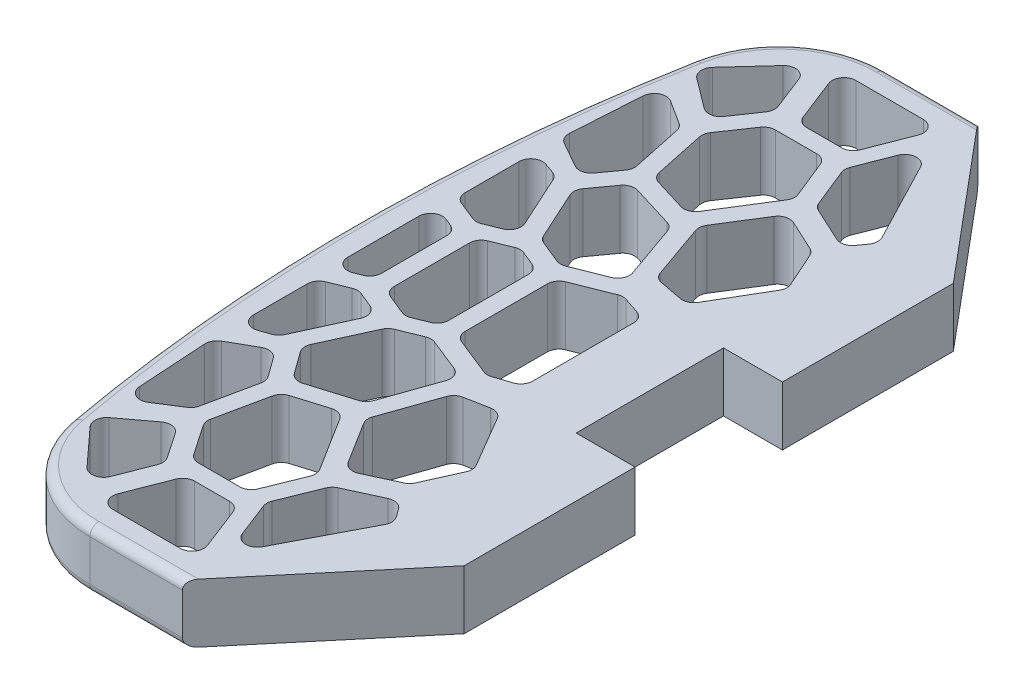
SolidWorks part; units mm, degrees
ref_plane "Спереди" through (0, 0, 0) normal (0, 0, 1) x (1, 0, 0)
ref_plane "Сверху" through (0, 0, 0) normal (0, 1, 0) x (1, 0, 0)
ref_plane "Справа" through (0, 0, 0) normal (1, 0, 0) x (0, 0, -1)
other "Configuration Table"
sketch "Sketch1" plane through (0, 0, 0) normal (0, 1, 0) x (1, 0, 0)
  line L0 (0, 83) -> (-43.6332, 135)
  line L1 (-120, 135) -> (0, 135) construction
  line L3 (-120, -135) -> (0, -135) construction
  line L4 (0, 135) -> (0, -135) construction
  line L5 (-43.6332, 135) -> (-75, 135)
  line L6 (0, -83) -> (-43.6332, -135)
  line L7 (0, 83) -> (0, 25)
  line L8 (0, 25) -> (-20, 25)
  line L9 (-20, 25) -> (-20, -25)
  line L10 (-20, -25) -> (0, -25)
  line L11 (-134.8601, 0) -> (61.7365, 0) construction
  line L12 (-89.1294, -199.9223) -> (-89.1294, 67.4111) construction
  line L13 (-120, 135) -> (-120, -135) construction
  line L14 (-43.6332, -135) -> (-75, -135)
  line L15 (0, -83) -> (0, -25)
  line L16 (-51.5835, -99.5519) -> (-47.044, -111.2449)
  line L17 (-39.7668, -111.6438) -> (-25.558, -84.3396)
  line L18 (-32.7123, -76.168) -> (-44.2897, -81.4925)
  line L19 (-46.3278, -83.6299) -> (-51.5641, -96.6076)
  line L20 (-76.1692, -126.0674) -> (-53.2432, -126.0674)
  line L21 (-49.5143, -120.6197) -> (-55.0229, -106.4306)
  line L22 (-58.7518, -103.8782) -> (-70.6335, -103.8782)
  line L23 (-74.3599, -106.4244) -> (-79.8956, -120.6136)
  line L24 (-104.3144, -105.6227) -> (-92.9037, -118.071)
  line L25 (-86.2286, -116.822) -> (-81.7314, -105.2948)
  line L26 (-82.1529, -101.5877) -> (-87.9561, -93.0762)
  line L27 (-93.6634, -92.1313) -> (-103.7682, -99.7216)
  line L28 (-110.4098, -12.0561) -> (-110.4098, 12.0561)
  line L29 (-104.9035, 15.7616) -> (-102.4473, 14.7632)
  line L30 (-99.9536, 11.0577) -> (-99.9536, -11.0577)
  line L31 (-102.4473, -14.7632) -> (-104.9035, -15.7616)
  line L32 (-91.46, 16.4616) -> (-84.9311, 19.1157)
  line L33 (-81.9184, 19.1157) -> (-77.2039, 17.1992)
  line L34 (-74.7102, 13.4937) -> (-74.7102, -13.4937)
  line L35 (-77.2039, -17.1992) -> (-81.9184, -19.1157)
  line L36 (-84.9311, -19.1157) -> (-91.46, -16.4616)
  line L37 (-93.9536, -12.7561) -> (-93.9536, 12.7561)
  line L38 (-68.7102, -13.9388) -> (-68.7102, 13.9388)
  line L39 (-66.193, 17.6539) -> (-53.5974, 22.6809)
  line L40 (-50.851, 22.761) -> (-45.3523, 20.93)
  line L41 (-42.6161, 17.1349) -> (-42.6161, -17.1349)
  line L42 (-45.3523, -20.93) -> (-50.851, -22.761)
  line L43 (-53.5974, -22.6809) -> (-66.193, -17.6539)
  line L44 (-109.4672, -45.085) -> (-109.4672, -26.7855)
  line L45 (-106.9735, -23.0799) -> (-100.549, -20.4683)
  line L46 (-97.5364, -20.4683) -> (-92.4294, -22.5443)
  line L47 (-90.2975, -27.912) -> (-98.3379, -45.5117)
  line L48 (-100.6417, -47.6203) -> (-104.1327, -48.8558)
  line L49 (-91.0282, -43.9506) -> (-83.4663, -27.3984)
  line L50 (-81.3343, -25.355) -> (-73.7854, -22.2863)
  line L51 (-70.7963, -22.2768) -> (-59.788, -26.6704)
  line L52 (-57.4974, -31.7129) -> (-63.8788, -49.851)
  line L53 (-66.4825, -52.3487) -> (-80.926, -56.7647)
  line L54 (-85.3376, -55.2823) -> (-90.6321, -47.9556)
  line L55 (-109.1859, -61.8731) -> (-107.7167, -85.4548)
  line L56 (-101.576, -88.5801) -> (-93.5679, -83.481)
  line L57 (-91.8022, -80.9315) -> (-88.1953, -63.8092)
  line L58 (-88.8673, -60.6419) -> (-93.373, -54.4066)
  line L59 (-98.5914, -53.2717) -> (-107.1699, -58.1467)
  line L60 (-59.2517, -54.778) -> (-52.7411, -36.2726)
  line L61 (-49.7099, -33.6696) -> (-41.8514, -32.1859)
  line L62 (-37.6591, -34.0926) -> (-27.4855, -51.4361)
  line L63 (-27.2853, -55.0953) -> (-32.5729, -66.8979)
  line L64 (-34.5425, -68.8922) -> (-45.0179, -73.7431)
  line L65 (-50.088, -72.2377) -> (-58.8677, -58.2299)
  line L66 (-86.0989, -82.9648) -> (-82.4552, -65.668)
  line L67 (-79.7106, -62.6673) -> (-68.759, -59.3189)
  line L68 (-64.2002, -61.0198) -> (-52.797, -79.2134)
  line L69 (-52.4768, -82.8344) -> (-57.5367, -95.3749)
  line L70 (-61.2462, -97.8782) -> (-75.3061, -97.8782)
  line L71 (-78.6111, -96.1315) -> (-85.4897, -86.0427)
  line L72 (-27.7933, -77.4671) -> (-25.8585, -80.1581)
  line L73 (-27.7933, 77.4671) -> (-25.8585, 80.1581)
  line L74 (-78.6111, 96.1315) -> (-85.4897, 86.0427)
  line L75 (-61.2462, 97.8782) -> (-75.3061, 97.8782)
  line L76 (-52.4768, 82.8344) -> (-57.5367, 95.3749)
  line L77 (-64.2002, 61.0198) -> (-52.797, 79.2134)
  line L78 (-79.7106, 62.6673) -> (-68.759, 59.3189)
  line L79 (-86.0989, 82.9648) -> (-82.4552, 65.668)
  line L80 (-50.088, 72.2377) -> (-58.8677, 58.2299)
  line L81 (-34.5425, 68.8922) -> (-45.0179, 73.7431)
  line L82 (-27.2853, 55.0953) -> (-32.5729, 66.8979)
  line L83 (-37.6591, 34.0926) -> (-27.4855, 51.4361)
  line L84 (-49.7099, 33.6696) -> (-41.8514, 32.1859)
  line L85 (-59.2517, 54.778) -> (-52.7411, 36.2726)
  line L86 (-98.5914, 53.2717) -> (-107.1699, 58.1467)
  line L87 (-88.8673, 60.6419) -> (-93.373, 54.4066)
  line L88 (-91.8022, 80.9315) -> (-88.1953, 63.8092)
  line L89 (-101.576, 88.5801) -> (-93.5679, 83.481)
  line L90 (-109.1859, 61.8731) -> (-107.7167, 85.4548)
  line L91 (-85.3376, 55.2823) -> (-90.6321, 47.9556)
  line L92 (-66.4825, 52.3487) -> (-80.926, 56.7647)
  line L93 (-57.4974, 31.7129) -> (-63.8788, 49.851)
  line L94 (-70.7963, 22.2768) -> (-59.788, 26.6704)
  line L95 (-81.3343, 25.355) -> (-73.7854, 22.2863)
  line L96 (-91.0282, 43.9506) -> (-83.4663, 27.3984)
  line L97 (-100.6417, 47.6203) -> (-104.1327, 48.8558)
  line L98 (-90.2975, 27.912) -> (-98.3379, 45.5117)
  line L99 (-97.5364, 20.4683) -> (-92.4294, 22.5443)
  line L100 (-106.9735, 23.0799) -> (-100.549, 20.4683)
  line L101 (-109.4672, 45.085) -> (-109.4672, 26.7855)
  line L102 (-93.6634, 92.1313) -> (-103.7682, 99.7216)
  line L103 (-82.1529, 101.5877) -> (-87.9561, 93.0762)
  line L104 (-86.2286, 116.822) -> (-81.7314, 105.2948)
  line L105 (-104.3144, 105.6227) -> (-92.9037, 118.071)
  line L106 (-74.3599, 106.4244) -> (-79.8956, 120.6136)
  line L107 (-58.7518, 103.8782) -> (-70.6335, 103.8782)
  line L108 (-49.5143, 120.6197) -> (-55.0229, 106.4306)
  line L109 (-76.1692, 126.0674) -> (-53.2432, 126.0674)
  line L110 (-46.3278, 83.6299) -> (-51.5641, 96.6076)
  line L111 (-32.7123, 76.168) -> (-44.2897, 81.4925)
  line L112 (-39.7668, 111.6438) -> (-25.558, 84.3396)
  line L113 (-51.5835, 99.5519) -> (-47.044, 111.2449)
  line L114 (-43.6332, 135) -> (-75, 135)
  arc A0 (-75, 135) -> (-110.4098, 105.4918) centre (-75, 99) ccw
  arc A1 (-110.4098, 105.4918) -> (-110.4098, -105.4918) centre (465, 0) ccw
  arc A2 (-75, -135) -> (-110.4098, -105.4918) centre (-75, -99) cw
  arc A3 (-59.2517, -54.778) -> (-58.8677, -58.2299) centre (-55.4784, -56.1056) ccw
  arc A4 (-52.7411, -36.2726) -> (-49.7099, -33.6696) centre (-48.9678, -37.6002) cw
  arc A5 (-41.8514, -32.1859) -> (-37.6591, -34.0926) centre (-41.1093, -36.1164) cw
  arc A6 (-27.4855, -51.4361) -> (-27.2853, -55.0953) centre (-30.9357, -53.4599) cw
  arc A7 (-32.5729, -66.8979) -> (-34.5425, -68.8922) centre (-36.2233, -65.2625) cw
  arc A8 (-45.0179, -73.7431) -> (-50.088, -72.2377) centre (-46.6987, -70.1134) cw
  arc A9 (-25.8585, -80.1581) -> (-25.558, -84.3396) centre (-29.1062, -82.4931) cw
  arc A10 (-27.7933, -77.4671) -> (-32.7123, -76.168) centre (-31.041, -79.8021) ccw
  arc A11 (-44.2897, -81.4925) -> (-46.3278, -83.6299) centre (-42.6184, -85.1266) ccw
  arc A12 (-51.5835, -99.5519) -> (-51.5641, -96.6076) centre (-47.8547, -98.1043) cw
  arc A13 (-47.044, -111.2449) -> (-39.7668, -111.6438) centre (-43.3151, -109.7973) ccw
  arc A14 (-53.2432, -126.0674) -> (-49.5143, -120.6197) centre (-53.2432, -122.0674) ccw
  arc A15 (-76.1692, -126.0674) -> (-79.8956, -120.6136) centre (-76.1692, -122.0674) cw
  arc A16 (-55.0229, -106.4306) -> (-58.7518, -103.8782) centre (-58.7518, -107.8782) ccw
  arc A17 (-70.6335, -103.8782) -> (-74.3599, -106.4244) centre (-70.6335, -107.8782) ccw
  arc A18 (-52.797, -79.2134) -> (-52.4768, -82.8344) centre (-56.1863, -81.3377) cw
  arc A19 (-57.5367, -95.3749) -> (-61.2462, -97.8782) centre (-61.2462, -93.8782) cw
  arc A20 (-75.3061, -97.8782) -> (-78.6111, -96.1315) centre (-75.3061, -93.8782) cw
  arc A21 (-86.0989, -82.9648) -> (-85.4897, -86.0427) centre (-82.1848, -83.7894) ccw
  arc A22 (-68.759, -59.3189) -> (-64.2002, -61.0198) centre (-67.5895, -63.1441) cw
  arc A23 (-82.4552, -65.668) -> (-79.7106, -62.6673) centre (-78.5411, -66.4925) cw
  arc A24 (-93.5679, -83.481) -> (-91.8022, -80.9315) centre (-95.7163, -80.1069) ccw
  arc A25 (-88.1953, -63.8092) -> (-88.8673, -60.6419) centre (-92.1094, -62.9847) ccw
  arc A26 (-93.373, -54.4066) -> (-98.5914, -53.2717) centre (-96.6151, -56.7494) ccw
  arc A27 (-81.7314, -105.2948) -> (-82.1529, -101.5877) centre (-85.4578, -103.841) ccw
  arc A28 (-87.9561, -93.0762) -> (-93.6634, -92.1313) centre (-91.261, -95.3295) ccw
  arc A29 (-92.9037, -118.071) -> (-86.2286, -116.822) centre (-89.955, -115.3682) ccw
  arc A30 (-104.3144, -105.6227) -> (-103.7682, -99.7216) centre (-101.3658, -102.9198) cw
  arc A31 (-109.1859, -61.8731) -> (-107.1699, -58.1467) centre (-105.1936, -61.6244) cw
  arc A32 (-107.7167, -85.4548) -> (-101.576, -88.5801) centre (-103.7245, -85.2061) ccw
  arc A33 (-80.926, -56.7647) -> (-85.3376, -55.2823) centre (-82.0955, -52.9395) cw
  arc A34 (-63.8788, -49.851) -> (-66.4825, -52.3487) centre (-67.6521, -48.5235) cw
  arc A35 (-59.788, -26.6704) -> (-57.4974, -31.7129) centre (-61.2707, -30.3854) cw
  arc A36 (-73.7854, -22.2863) -> (-70.7963, -22.2768) centre (-72.279, -25.9919) cw
  arc A37 (-83.4663, -27.3984) -> (-81.3343, -25.355) centre (-79.828, -29.0606) cw
  arc A38 (-91.0282, -43.9506) -> (-90.6321, -47.9556) centre (-87.3899, -45.6128) ccw
  arc A39 (-98.3379, -45.5117) -> (-100.6417, -47.6203) centre (-101.9762, -43.8495) cw
  arc A40 (-109.4672, -45.085) -> (-104.1327, -48.8558) centre (-105.4672, -45.085) ccw
  arc A41 (-92.4294, -22.5443) -> (-90.2975, -27.912) centre (-93.9358, -26.2499) cw
  arc A42 (-100.549, -20.4683) -> (-97.5364, -20.4683) centre (-99.0427, -24.1739) cw
  arc A43 (-109.4672, -26.7855) -> (-106.9735, -23.0799) centre (-105.4672, -26.7855) cw
  arc A44 (-74.7102, -13.4937) -> (-77.2039, -17.1992) centre (-78.7102, -13.4937) cw
  arc A45 (-91.46, -16.4616) -> (-93.9536, -12.7561) centre (-89.9536, -12.7561) cw
  arc A46 (-81.9184, -19.1157) -> (-84.9311, -19.1157) centre (-83.4248, -15.4101) cw
  arc A47 (-42.6161, -17.1349) -> (-45.3523, -20.93) centre (-46.6161, -17.1349) cw
  arc A48 (-50.851, -22.761) -> (-53.5974, -22.6809) centre (-52.1147, -18.9659) cw
  arc A49 (-68.7102, -13.9388) -> (-66.193, -17.6539) centre (-64.7102, -13.9388) ccw
  arc A50 (-45.3523, 20.93) -> (-42.6161, 17.1349) centre (-46.6161, 17.1349) cw
  arc A51 (-53.5974, 22.6809) -> (-50.851, 22.761) centre (-52.1147, 18.9659) cw
  arc A52 (-68.7102, 13.9388) -> (-66.193, 17.6539) centre (-64.7102, 13.9388) cw
  arc A53 (-77.2039, 17.1992) -> (-74.7102, 13.4937) centre (-78.7102, 13.4937) cw
  arc A54 (-84.9311, 19.1157) -> (-81.9184, 19.1157) centre (-83.4248, 15.4101) cw
  arc A55 (-91.46, 16.4616) -> (-93.9536, 12.7561) centre (-89.9536, 12.7561) ccw
  arc A56 (-99.9536, -11.0577) -> (-102.4473, -14.7632) centre (-103.9536, -11.0577) cw
  arc A57 (-110.4098, -12.0561) -> (-104.9035, -15.7616) centre (-106.4098, -12.0561) ccw
  arc A58 (-102.4473, 14.7632) -> (-99.9536, 11.0577) centre (-103.9536, 11.0577) cw
  arc A59 (-110.4098, 12.0561) -> (-104.9035, 15.7616) centre (-106.4098, 12.0561) cw
  arc A60 (-109.4672, 26.7855) -> (-106.9735, 23.0799) centre (-105.4672, 26.7855) ccw
  arc A61 (-92.4294, 22.5443) -> (-90.2975, 27.912) centre (-93.9358, 26.2499) ccw
  arc A62 (-109.4672, 45.085) -> (-104.1327, 48.8558) centre (-105.4672, 45.085) cw
  arc A63 (-98.3379, 45.5117) -> (-100.6417, 47.6203) centre (-101.9762, 43.8495) ccw
  arc A64 (-91.0282, 43.9506) -> (-90.6321, 47.9556) centre (-87.3899, 45.6128) cw
  arc A65 (-83.4663, 27.3984) -> (-81.3343, 25.355) centre (-79.828, 29.0606) ccw
  arc A66 (-73.7854, 22.2863) -> (-70.7963, 22.2768) centre (-72.279, 25.9919) ccw
  arc A67 (-59.788, 26.6704) -> (-57.4974, 31.7129) centre (-61.2707, 30.3854) ccw
  arc A68 (-63.8788, 49.851) -> (-66.4825, 52.3487) centre (-67.6521, 48.5235) ccw
  arc A69 (-80.926, 56.7647) -> (-85.3376, 55.2823) centre (-82.0955, 52.9395) ccw
  arc A70 (-107.7167, 85.4548) -> (-101.576, 88.5801) centre (-103.7245, 85.2061) cw
  arc A71 (-109.1859, 61.8731) -> (-107.1699, 58.1467) centre (-105.1936, 61.6244) ccw
  arc A72 (-104.3144, 105.6227) -> (-103.7682, 99.7216) centre (-101.3658, 102.9198) ccw
  arc A73 (-92.9037, 118.071) -> (-86.2286, 116.822) centre (-89.955, 115.3682) cw
  arc A74 (-87.9561, 93.0762) -> (-93.6634, 92.1313) centre (-91.261, 95.3295) cw
  arc A75 (-81.7314, 105.2948) -> (-82.1529, 101.5877) centre (-85.4578, 103.841) cw
  arc A76 (-93.373, 54.4066) -> (-98.5914, 53.2717) centre (-96.6151, 56.7494) cw
  arc A77 (-88.1953, 63.8092) -> (-88.8673, 60.6419) centre (-92.1094, 62.9847) cw
  arc A78 (-93.5679, 83.481) -> (-91.8022, 80.9315) centre (-95.7163, 80.1069) cw
  arc A79 (-82.4552, 65.668) -> (-79.7106, 62.6673) centre (-78.5411, 66.4925) ccw
  arc A80 (-68.759, 59.3189) -> (-64.2002, 61.0198) centre (-67.5895, 63.1441) ccw
  arc A81 (-86.0989, 82.9648) -> (-85.4897, 86.0427) centre (-82.1848, 83.7894) cw
  arc A82 (-75.3061, 97.8782) -> (-78.6111, 96.1315) centre (-75.3061, 93.8782) ccw
  arc A83 (-57.5367, 95.3749) -> (-61.2462, 97.8782) centre (-61.2462, 93.8782) ccw
  arc A84 (-52.797, 79.2134) -> (-52.4768, 82.8344) centre (-56.1863, 81.3377) ccw
  arc A85 (-70.6335, 103.8782) -> (-74.3599, 106.4244) centre (-70.6335, 107.8782) cw
  arc A86 (-55.0229, 106.4306) -> (-58.7518, 103.8782) centre (-58.7518, 107.8782) cw
  arc A87 (-76.1692, 126.0674) -> (-79.8956, 120.6136) centre (-76.1692, 122.0674) ccw
  arc A88 (-53.2432, 126.0674) -> (-49.5143, 120.6197) centre (-53.2432, 122.0674) cw
  arc A89 (-47.044, 111.2449) -> (-39.7668, 111.6438) centre (-43.3151, 109.7973) cw
  arc A90 (-51.5835, 99.5519) -> (-51.5641, 96.6076) centre (-47.8547, 98.1043) ccw
  arc A91 (-44.2897, 81.4925) -> (-46.3278, 83.6299) centre (-42.6184, 85.1266) cw
  arc A92 (-27.7933, 77.4671) -> (-32.7123, 76.168) centre (-31.041, 79.8021) cw
  arc A93 (-25.8585, 80.1581) -> (-25.558, 84.3396) centre (-29.1062, 82.4931) ccw
  arc A94 (-45.0179, 73.7431) -> (-50.088, 72.2377) centre (-46.6987, 70.1134) ccw
  arc A95 (-32.5729, 66.8979) -> (-34.5425, 68.8922) centre (-36.2233, 65.2625) ccw
  arc A96 (-27.4855, 51.4361) -> (-27.2853, 55.0953) centre (-30.9357, 53.4599) ccw
  arc A97 (-41.8514, 32.1859) -> (-37.6591, 34.0926) centre (-41.1093, 36.1164) ccw
  arc A98 (-52.7411, 36.2726) -> (-49.7099, 33.6696) centre (-48.9678, 37.6002) ccw
  arc A99 (-59.2517, 54.778) -> (-58.8677, 58.2299) centre (-55.4784, 56.1056) cw
  arc A100 (-100.549, 20.4683) -> (-97.5364, 20.4683) centre (-99.0427, 24.1739) ccw
  point P155 (-99.0427, -47.0544)
  point P158 (-109.4672, -50.7438)
  point P193 (-110.4098, -18)
  point P198 (-110.4098, 18)
  point P199 (-100.3678, -46.2956)
  point P200 (0, 0)
  point P321 (-99.0427, 47.0544)
  dimension "D7" = 36
  dimension "D25" = 4
  dimension "D1" = 120
  dimension "D2" = 270
  dimension "D3" = 40
  dimension "D4" = 20
  dimension "D5" = 50
  dimension "D6" = 58
  dimension "D8" = 75
  dimension "D9" = 6
  dimension "D10" = 6
  dimension "D11" = 6
  dimension "D12" = 6
  dimension "D13" = 6
  dimension "D14" = 6
  dimension "D15" = 6
  dimension "D16" = 6
  dimension "D17" = 6
  dimension "D18" = 6
  dimension "D19" = 6
  dimension "D20" = 36
  dimension "D21" = 6
  dimension "D22" = 6
  dimension "D23" = 6
  dimension "D24" = 6
extrude "Boss-Extrude1" add sketch "Sketch1" along normal mid plane 20 contours A2 L14 L6 L15 L10 L9 L8 L7 L0 L5 A0 A1 A100 L100 A60 L101 A62 L97 A63 L98 A61 L99 A93 L73 A92 L111 A91 L110 A90 L113 A89 L112 A84 L77 A80 L78 A79 L79 A81 L74 A82 L75 A83 L76 A69 L92 A68
fillet "Fillet1" radius 3 10 edges at (-59.3166, 10, -135) (-98.0466, 10, -126.656) (-59.3166, 10, 135) (-98.0466, 10, 126.656) (-59.3166, -10, -135) (-98.0466, -10, -126.656) (-59.3166, -10, 135) (-98.0466, -10, 126.656) (-120, 10, 0) (-120, -10, 0)
equation "\"D10@Sketch1\"=\"D9@Sketch1\""
equation "\"D11@Sketch1\"=\"D9@Sketch1\""
equation "\"D12@Sketch1\"=\"D9@Sketch1\""
equation "\"D13@Sketch1\"=\"D9@Sketch1\""
equation "\"D14@Sketch1\"=\"D9@Sketch1\""
equation "\"D15@Sketch1\"=\"D9@Sketch1\""
equation "\"D16@Sketch1\"=\"D9@Sketch1\""
equation "\"D17@Sketch1\"=\"D9@Sketch1\""
equation "\"D18@Sketch1\"=\"D9@Sketch1\""
equation "\"D19@Sketch1\"=\"D9@Sketch1\""
equation "\"D21@Sketch1\"=\"D9@Sketch1\""
equation "\"D22@Sketch1\"=\"D9@Sketch1\""
equation "\"D23@Sketch1\"=\"D9@Sketch1\""
equation "\"D24@Sketch1\"=\"D9@Sketch1\""
